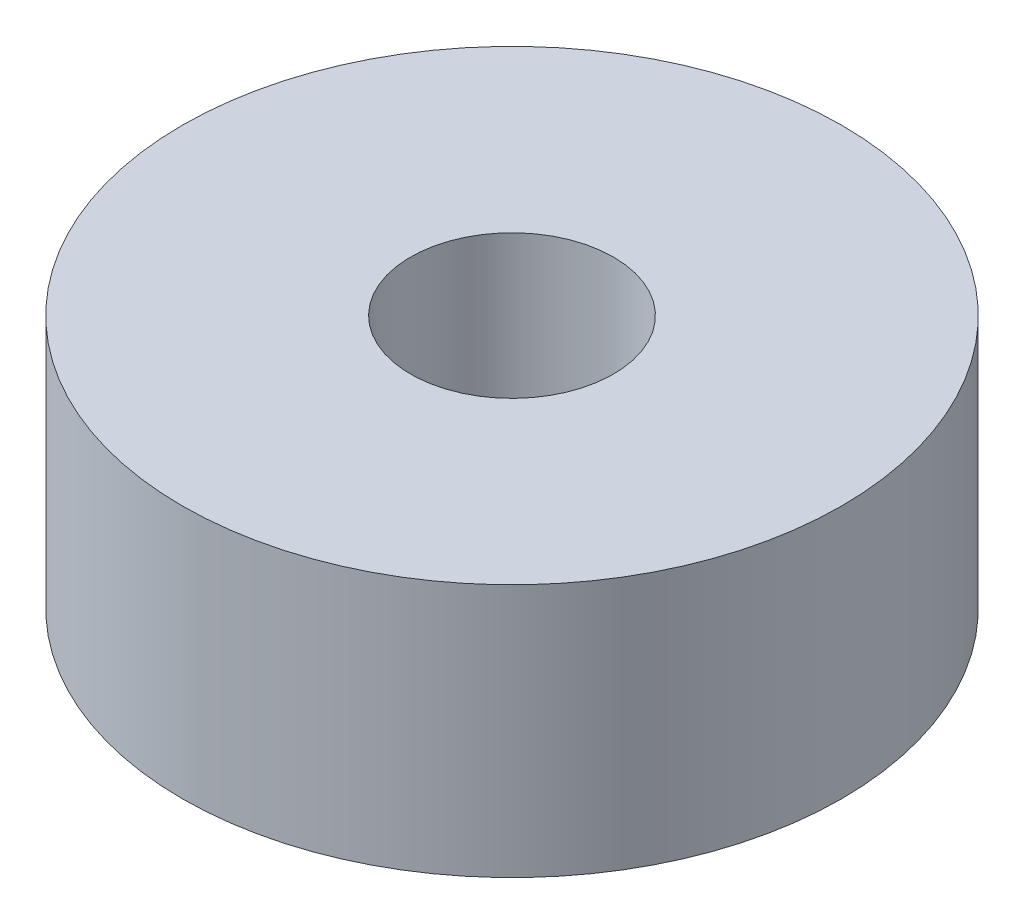
SolidWorks part; units mm, degrees
ref_plane "Plan de face" through (0, 0, 0) normal (0, 0, 1) x (1, 0, 0)
ref_plane "Plan de dessus" through (0, 0, 0) normal (0, 1, 0) x (1, 0, 0)
ref_plane "Plan de droite" through (0, 0, 0) normal (1, 0, 0) x (0, 0, -1)
sketch "Esquisse1" plane through (0, 0, 0) normal (0, 0, 1) x (1, 0, 0)
  line L0 (0, -2.3988) -> (0, 4.4273) construction
  line L2 (2, 2.5) -> (6.5, 2.5)
  line L3 (2, 2.5) -> (2, -2.5)
  line L4 (2, -2.5) -> (6.5, -2.5)
  line L5 (6.5, 2.5) -> (6.5, -2.5)
  point P7 (2, 0)
  dimension "D1" = 4
  dimension "D2" = 13
  dimension "D3" = 5
revolve "Révolution1" add sketch "Esquisse1" angle 360 about L0
